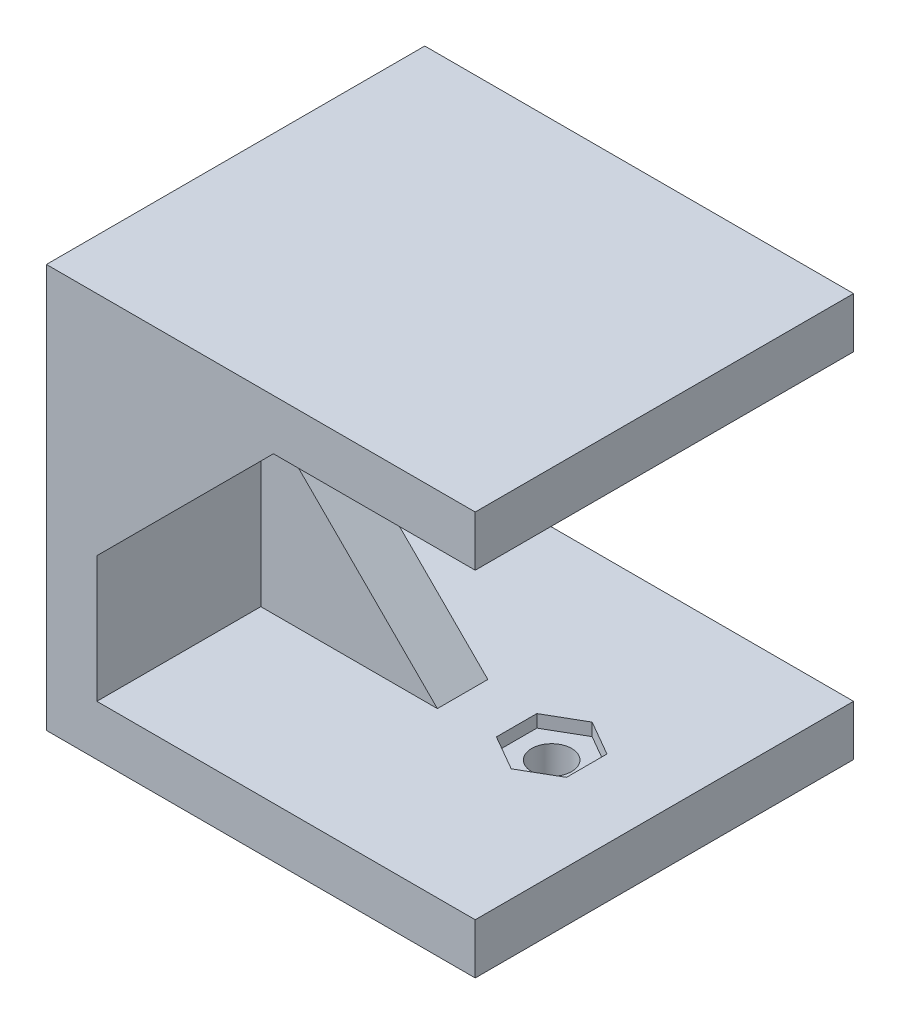
SolidWorks part; units mm, degrees
material "ABS"
ref_plane "Front Plane" through (0, 0, 0) normal (0, 0, 1) x (1, 0, 0)
ref_plane "Top Plane" through (0, 0, 0) normal (0, 1, 0) x (1, 0, 0)
ref_plane "Right Plane" through (0, 0, 0) normal (1, 0, 0) x (0, 0, -1)
sketch "Sketch1" plane through (0, 0, 0) normal (0, 1, 0) x (1, 0, 0)
  line L1 (0, 0) -> (68, 0)
  line L2 (0, 0) -> (0, 60)
  line L3 (0, 60) -> (68, 60)
  line L4 (68, 0) -> (68, 60)
  dimension "D1" = 68
  dimension "D2" = 60
extrude "Boss-Extrude1" add sketch "Sketch1" along normal blind 8
sketch "Sketch4" plane through (0, 8, 0) normal (0, 1, 0) x (1, 0, 0)
  line L0 (8, 0) -> (8, 60)
  line L1 (0, 0) -> (68, 0) construction
  line L2 (68, 60) -> (0, 60) construction
  line L3 (0, 60) -> (0, 0) construction
  line L4 (0, 0) -> (8, 0)
  line L5 (0, 60) -> (0, 0)
  line L6 (8, 60) -> (0, 60)
  dimension "D1" = 8
extrude "Boss-Extrude2" add sketch "Sketch4" along normal blind 56
sketch "Sketch5" plane through (0, 8, 0) normal (0, 1, 0) x (1, 0, 0)
  line L1 (8, 0) -> (68, 0) construction
  line L3 (68, 0) -> (68, 60) construction
  circle A0 centre (50.125, 30) radius 3.175
  dimension "D1" = 6.35
  dimension "D2" = 30
  dimension "D3" = 17.875
extrude "Cut-Extrude1" cut sketch "Sketch5" against normal blind 8
sketch "Sketch6" plane through (8, 0, 0) normal (1, 0, 0) x (0, 0, -1)
  line L0 (0, 64) -> (60, 64) construction
  line L1 (0, 64) -> (60, 64)
  line L2 (0, 56) -> (60, 56)
  line L3 (0, 56) -> (0, 64)
  line L4 (60, 64) -> (60, 56)
  dimension "D1" = 8
extrude "Boss-Extrude3" add sketch "Sketch6" along normal up to surface (60 mm away) up to face at (68, 4, -30)
sketch "Sketch7" plane through (0, 0, 0) normal (0, 0, 1) x (1, 0, 0)
  line L0 (8, 56) -> (8, 8) construction
  line L2 (8, 56) -> (8, 28)
  line L4 (8, 28) -> (36, 56)
  line L6 (68, 56) -> (8, 56) construction
  line L7 (8, 56) -> (36, 56)
  dimension "D1" = 45
  dimension "D2" = 28
extrude "Boss-Extrude4" add sketch "Sketch7" against normal blind 8
ref_plane "Plane1" through (0, 0, -30) normal (0, 0, 1) x (1, 0, 0)
mirror "Mirror1" about plane through (0, 0, -30) normal (0, 0, 1) of "Boss-Extrude4"
sketch "Sketch8" plane through (0, 0, -30) normal (0, 0, 1) x (1, 0, 0)
  line L0 (8, 28) -> (8, 8) construction
  line L1 (8, 8) -> (68, 8) construction
  line L2 (8, 36) -> (8, 8)
  line L3 (8, 8) -> (36, 8)
  line L4 (8, 36) -> (36, 8)
  dimension "D1" = 28
  dimension "D2" = 45
extrude "Boss-Extrude5" add sketch "Sketch8" along normal blind 4 and the other way blind 4
sketch "Sketch9" plane through (0, 8, 0) normal (0, 1, 0) x (1, 0, 0)
  line L0 (50.125, 36.4158) -> (44.5687, 33.2079) construction
  line L1 (50.125, 36.4158) -> (44.5687, 33.2079)
  line L2 (44.5687, 33.2079) -> (44.5687, 26.7921) construction
  line L3 (44.5687, 33.2079) -> (44.5687, 26.7921)
  line L4 (44.5687, 26.7921) -> (50.125, 23.5842) construction
  line L5 (50.125, 23.5842) -> (55.6812, 26.7921) construction
  line L6 (55.6812, 26.7921) -> (55.6812, 33.2079) construction
  line L7 (55.6812, 33.2079) -> (50.125, 36.4158) construction
  line L24 (44.5687, 26.7921) -> (50.125, 23.5842)
  line L25 (50.125, 23.5842) -> (55.6812, 26.7921)
  line L26 (55.6812, 26.7921) -> (55.6812, 33.2079)
  line L27 (55.6812, 33.2079) -> (50.125, 36.4158)
extrude "Cut-Extrude2" cut sketch "Sketch9" against normal blind 2
